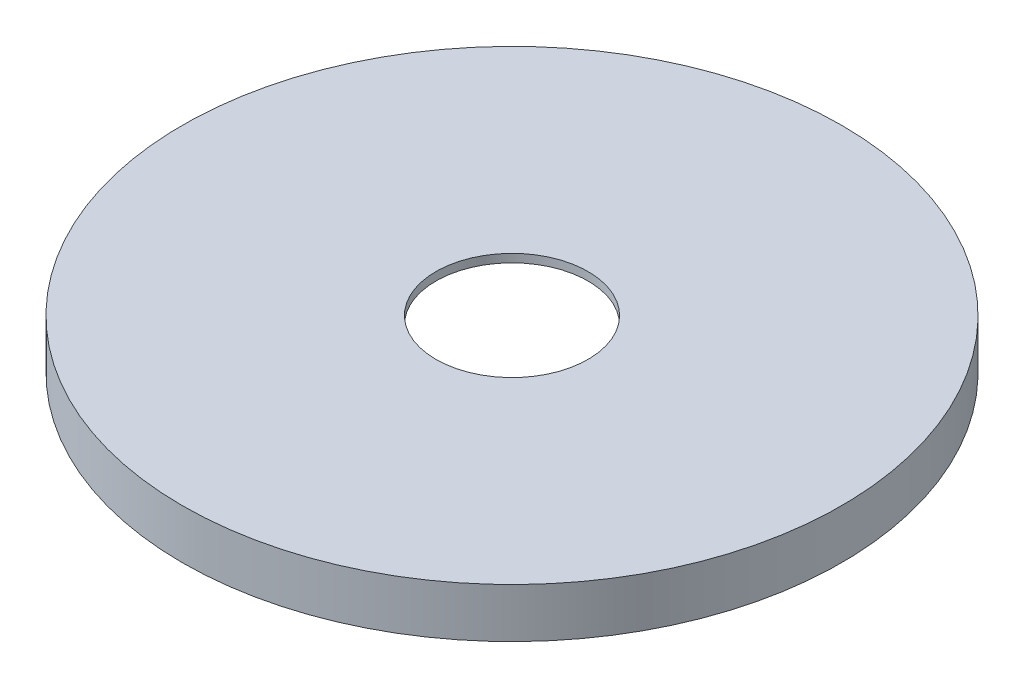
SolidWorks part; units mm, degrees
ref_plane "Front Plane" through (0, 0, 0) normal (0, 0, 1) x (1, 0, 0)
ref_plane "Top Plane" through (0, 0, 0) normal (0, 1, 0) x (1, 0, 0)
ref_plane "Right Plane" through (0, 0, 0) normal (1, 0, 0) x (0, 0, -1)
sketch "Sketch1" plane through (-3.3431, -71.8294, 16.9117) normal (0, 0, 1) x (1, 0, 0)
  line L0 (3.3431, 71.8294) -> (3.3431, 85.3592) construction
  line L2 (-36.6569, 65.8294) -> (-36.6569, 71.8294)
  line L3 (-36.6569, 71.8294) -> (3.3431, 71.8294)
  point P2 (0, 0)
  point P3 (0, 0)
  dimension "D1" = 40
  dimension "D2" = 6
revolve "Revolve-Thin1" add sketch "Sketch1" angle 360 about L0
sketch "Sketch2" plane through (0, 0, 0) normal (0, 1, 0) x (1, 0, 0)
  circle A0 centre (0, -16.9117) radius 9.2366
  circle A1 centre (0, -16.9117) radius 40 construction
extrude "Cut-Extrude1" cut sketch "Sketch2" against normal up to surface (1 mm away) up to face at (0, -1, -22.0883)
